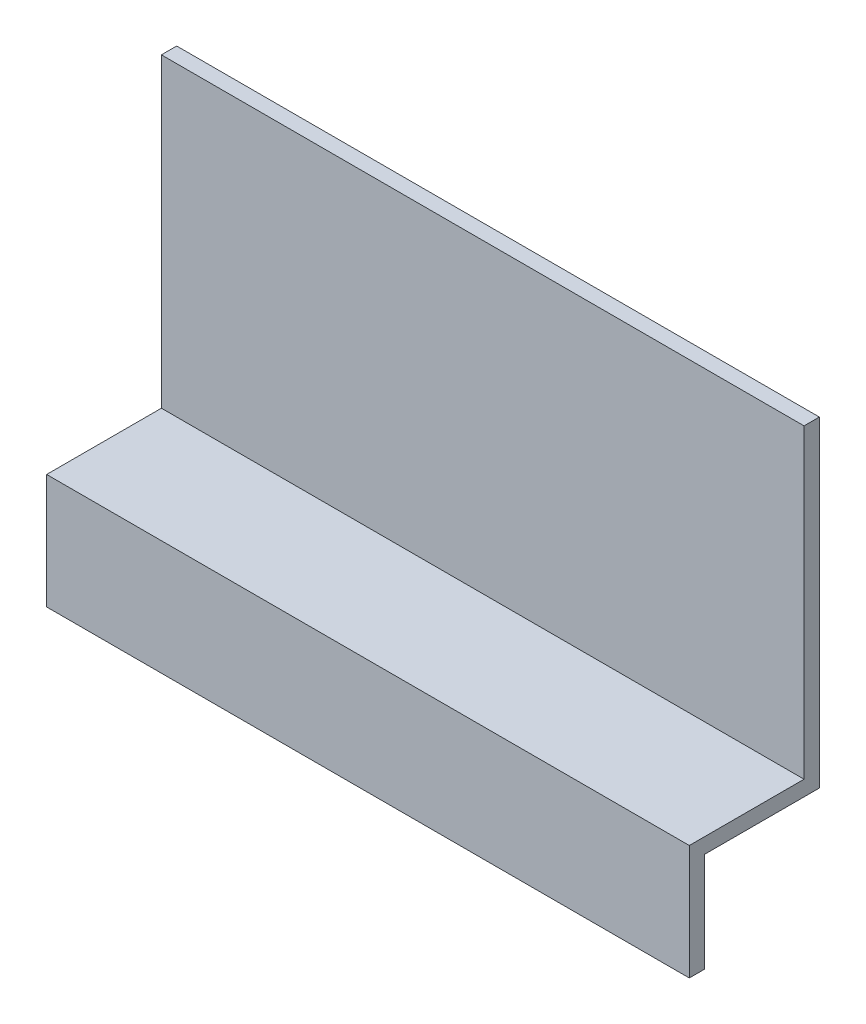
SolidWorks part; units mm, degrees
ref_plane "Front Plane" through (0, 0, 0) normal (0, 0, 1) x (1, 0, 0)
ref_plane "Top Plane" through (0, 0, 0) normal (0, 1, 0) x (1, 0, 0)
ref_plane "Right Plane" through (0, 0, 0) normal (1, 0, 0) x (0, 0, -1)
sketch "Sketch1" plane through (0, 0, 0) normal (1, 0, 0) x (0, 0, -1)
  line L0 (0, 0) -> (0, 13)
  line L5 (13, 15) -> (-2, 15)
  line L6 (-2, 15) -> (-2, 0)
  line L7 (-2, 0) -> (0, 0)
  line L9 (13, 15) -> (13, 55)
  line L10 (13, 55) -> (15, 55)
  line L11 (15, 55) -> (15, 13)
  line L12 (0, 13) -> (15, 13)
  dimension "D1" = 2
  dimension "D2" = 2
  dimension "D3" = 42
  dimension "D4" = 15
  dimension "D5" = 15
  dimension "D6" = 2
extrude "Boss-Extrude1" add sketch "Sketch1" against normal blind 84
